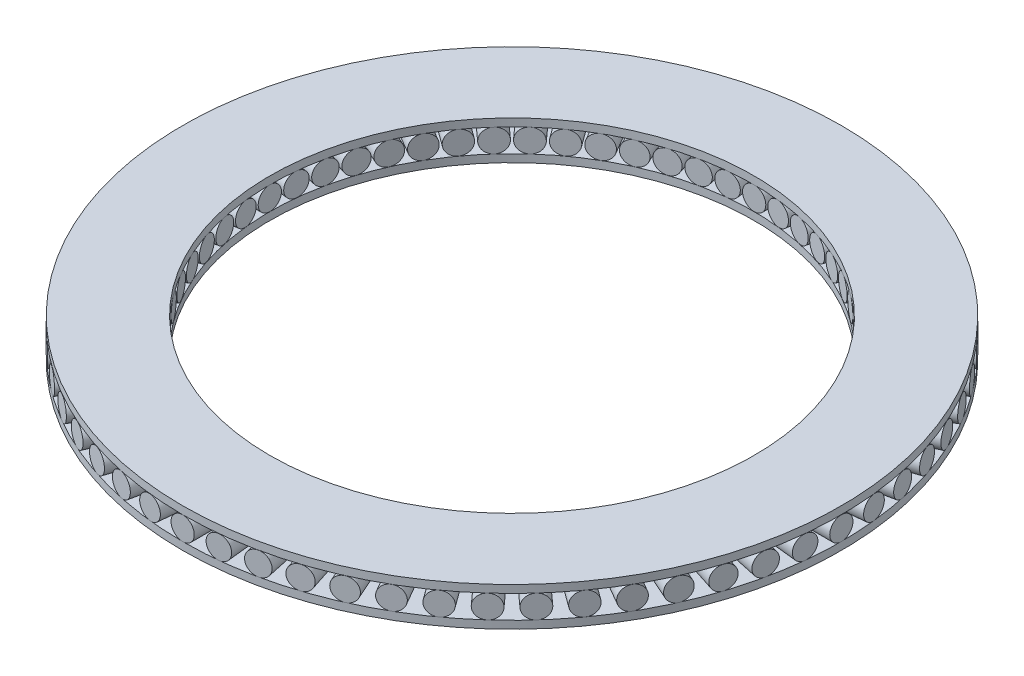
SolidWorks part; units mm, degrees
ref_plane "前视基准面" through (0, 0, 0) normal (0, 0, 1) x (1, 0, 0)
ref_plane "上视基准面" through (0, 0, 0) normal (0, 1, 0) x (1, 0, 0)
ref_plane "右视基准面" through (0, 0, 0) normal (1, 0, 0) x (0, 0, -1)
sketch "草图1" plane through (0, 0, 0) normal (0, 1, 0) x (1, 0, 0)
  circle A0 centre (0, 0) radius 31.25
  circle A1 centre (0, 0) radius 42.5
  dimension "D1" = 62.5
  dimension "D2" = 85
extrude "凸台-拉伸1" add sketch "草图1" along normal blind 1
sketch "草图2" plane through (0, 0, 0) normal (1, 0, 0) x (0, 0, -1)
  line L0 (0, 0) -> (0, 2.5) construction
  circle A0 centre (0, 2.5) radius 1.5
  point P4 (0, 0)
extrude "凸台-拉伸2" add sketch "草图2" along normal blind 11.25 from offset 31.25 separate body
pattern_circular "阵列(圆周)1" count 60 every 6 about axis through (0, 0, 0) along (0, 1, 0) of bodies 102
sketch "草图3" plane through (0, 0, 0) normal (0, 1, 0) x (1, 0, 0)
  circle A1 centre (0, 0) radius 42.5
  circle A2 centre (0, 0) radius 31.25
  dimension "D1" = 62.5
  dimension "D2" = 85
extrude "凸台-拉伸3" add sketch "草图3" along normal blind 1 from offset 4 separate body
